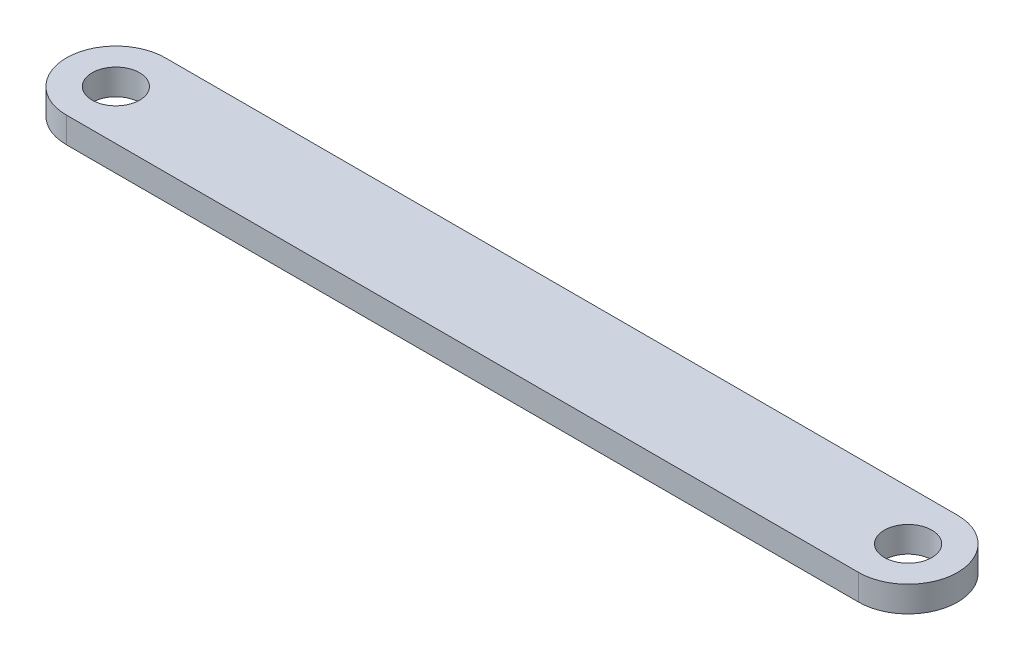
SolidWorks part; units mm, degrees
ref_plane "Front Plane" through (0, 0, 0) normal (0, 0, 1) x (1, 0, 0)
ref_plane "Top Plane" through (0, 0, 0) normal (0, 1, 0) x (1, 0, 0)
ref_plane "Right Plane" through (0, 0, 0) normal (1, 0, 0) x (0, 0, -1)
sketch "Sketch1" plane through (0, 0, 0) normal (0, 1, 0) x (1, 0, 0)
  line L0 (0, 0) -> (200, 0) construction
  line L1 (0, 12.5) -> (200, 12.5)
  line L2 (0, -12.5) -> (200, -12.5)
  arc A0 (0, 12.5) -> (0, -12.5) centre (0, 0) ccw
  arc A1 (200, -12.5) -> (200, 12.5) centre (200, 0) ccw
  circle A2 centre (0, 0) radius 6
  circle A3 centre (200, 0) radius 6
  point P3 (100, 0)
  dimension "D2" = 25
  dimension "D3" = 12
  dimension "D1" = 200
extrude "Boss-Extrude1" add sketch "Sketch1" along normal blind 6.5
